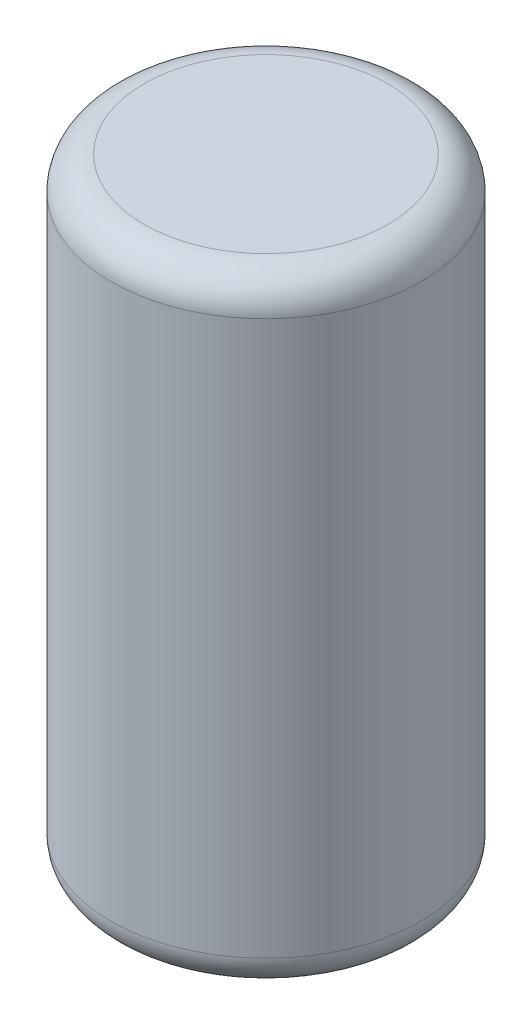
SolidWorks part; units mm, degrees
ref_plane "Front Plane" through (0, 0, 0) normal (0, 0, 1) x (1, 0, 0)
ref_plane "Top Plane" through (0, 0, 0) normal (0, 1, 0) x (1, 0, 0)
ref_plane "Right Plane" through (0, 0, 0) normal (1, 0, 0) x (0, 0, -1)
sketch "Sketch1" plane through (0, 0, 0) normal (0, 1, 0) x (1, 0, 0)
  circle A0 centre (0, 0) radius 1.1906
  dimension "D1" = 2.3813
extrude "Boss-Extrude1" add sketch "Sketch1" along normal blind 4.7625
fillet "Fillet2" radius 0.254 2 edges at (0, 0, 1.1906) (0, 4.7625, 1.1906)
